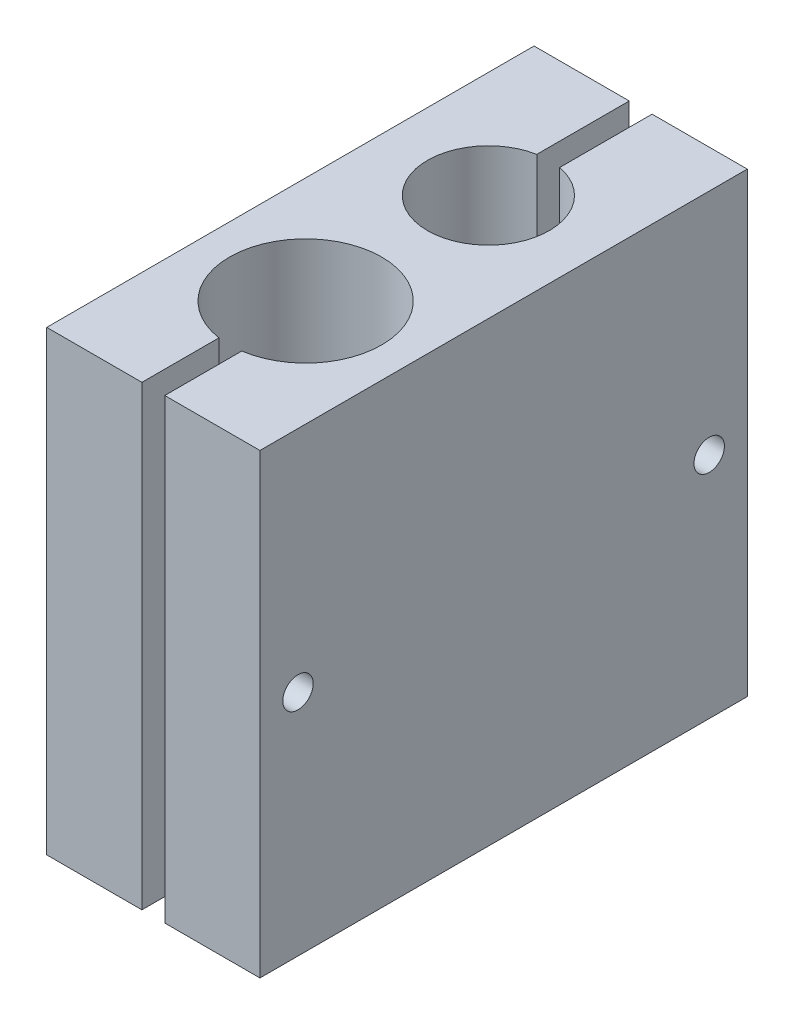
SolidWorks part; units mm, degrees
ref_plane "Front Plane" through (0, 0, 0) normal (0, 0, 1) x (1, 0, 0)
ref_plane "Top Plane" through (0, 0, 0) normal (0, 1, 0) x (1, 0, 0)
ref_plane "Right Plane" through (0, 0, 0) normal (1, 0, 0) x (0, 0, -1)
sketch "Sketch1" plane through (0, 0, 0) normal (0, 1, 0) x (1, 0, 0)
  line L0 (0, 0) -> (0, 12) construction
  line L2 (-7, -10) -> (7, -10)
  line L3 (-7, -10) -> (-7, 22)
  line L4 (-7, 22) -> (7, 22)
  line L5 (7, -10) -> (7, 22)
  circle A0 centre (0, 0) radius 3.4
  circle A1 centre (0, 12) radius 4
  point P11 (0, -10)
  point P12 (0, 22)
  dimension "D1" = 6.8
  dimension "D2" = 8
  dimension "D6" = 10
  dimension "D3" = 12
  dimension "D4" = 14
  dimension "D5" = 10
  dimension "D7" = 14
extrude "Boss-Extrude1" add sketch "Sketch1" along normal blind 30
sketch "Sketch2" plane through (0, 30, 0) normal (0, 1, 0) x (1, 0, 0)
  circle A0 centre (0, 0) radius 5
  dimension "D1" = 10
extrude "Cut-Extrude1" cut sketch "Sketch2" against normal blind 8 contours A0
sketch "Sketch3" plane through (0, 0, 0) normal (0, -1, 0) x (1, 0, 0)
  line L0 (7, -22) -> (-7, -22) construction
  line L1 (-7, 10) -> (7, 10) construction
  line L2 (-0.75, 20) -> (0.75, 20)
  line L3 (-0.75, 20) -> (-0.75, 0)
  line L4 (-0.75, 0) -> (0.75, 0)
  line L5 (0.75, 20) -> (0.75, 0)
  line L6 (-0.75, 20) -> (0.75, 0) construction
  line L7 (-0.75, 0) -> (0.75, 20) construction
  line L9 (0.75, -32) -> (-0.75, -32)
  line L10 (0.75, -32) -> (0.75, -12)
  line L11 (0.75, -12) -> (-0.75, -12)
  line L12 (-0.75, -32) -> (-0.75, -12)
  line L13 (0.75, -32) -> (-0.75, -12) construction
  line L14 (0.75, -12) -> (-0.75, -32) construction
  point P0 (0, 10)
  point P1 (0, 10)
  point P2 (0, 0)
  point P9 (0, -22)
  point P10 (0, -22)
  point P17 (0, -12)
  dimension "D1" = 1.5
  dimension "D4" = 1.5
extrude "Cut-Extrude2" cut sketch "Sketch3" against normal through all
sketch "Sketch4" plane through (-7, 0, 0) normal (-1, 0, 0) x (0, 0, 1)
  line L0 (10, 15) -> (-22, 15) construction
  line L1 (10, 30) -> (10, 0) construction
  line L2 (-22, 30) -> (-22, 0) construction
  circle A0 centre (7.5, 15) radius 1
  circle A1 centre (-19.5, 15) radius 1
  dimension "D1" = 2
  dimension "D2" = 2
  dimension "D3" = 2.5
  dimension "D4" = 2.5
extrude "Cut-Extrude3" cut sketch "Sketch4" against normal through all
